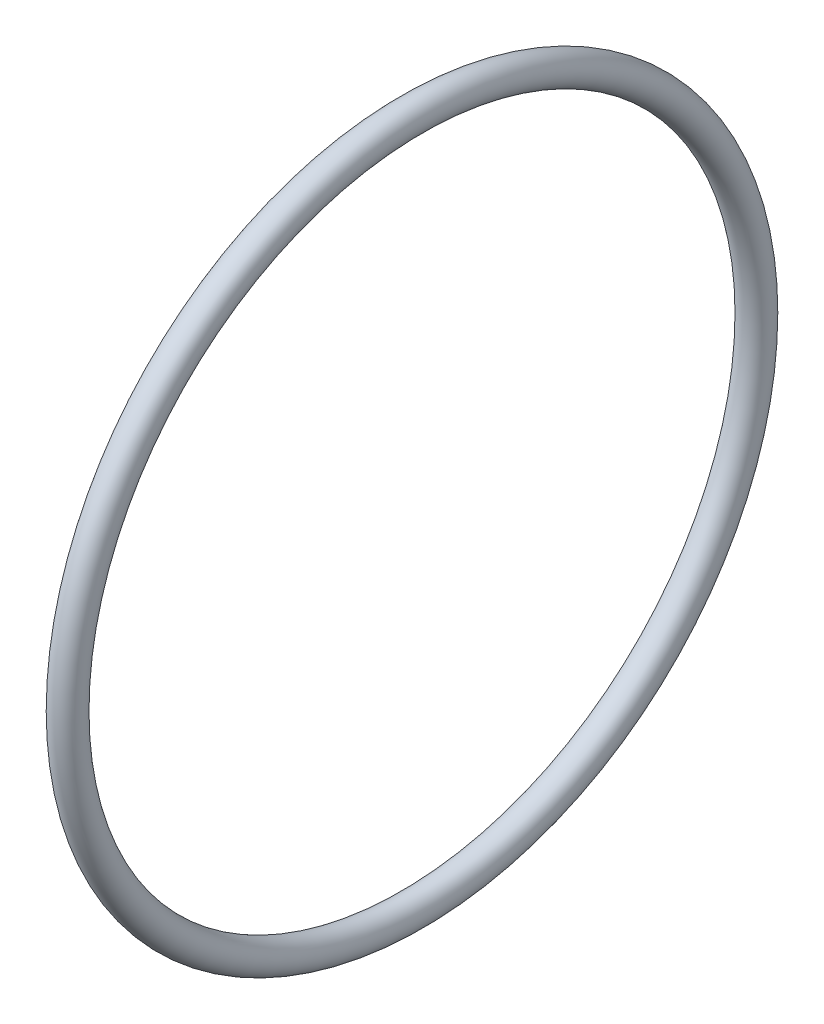
SolidWorks part; units mm, degrees
ref_plane "Plan1" through (0, 0, 0) normal (0, 0, 1) x (1, 0, 0)
ref_plane "Plan2" through (0, 0, 0) normal (0, 1, 0) x (1, 0, 0)
ref_plane "Plan3" through (0, 0, 0) normal (1, 0, 0) x (0, 0, -1)
sketch "Esquisse1" plane through (0, 0, 0) normal (0, 0, 1) x (1, 0, 0)
  line L0 (0, 0) -> (30, 0) construction
  circle A0 centre (2, 45.5) radius 2
  dimension "D1" = 4
  dimension "D2" = 45.5
  dimension "D3" = 2
revolve "Base-Révolution" add sketch "Esquisse1" angle 360 about L0
ref_plane "Plan4" through (0, 0, 45.5) normal (-1, 0, 0) x (0, 0, 1)
sketch "Esquisse2" plane through (0, 0, 0) normal (0, 1, 0) x (1, 0, 0)
  line L0 (0, 0) -> (31.2779, 0) construction
